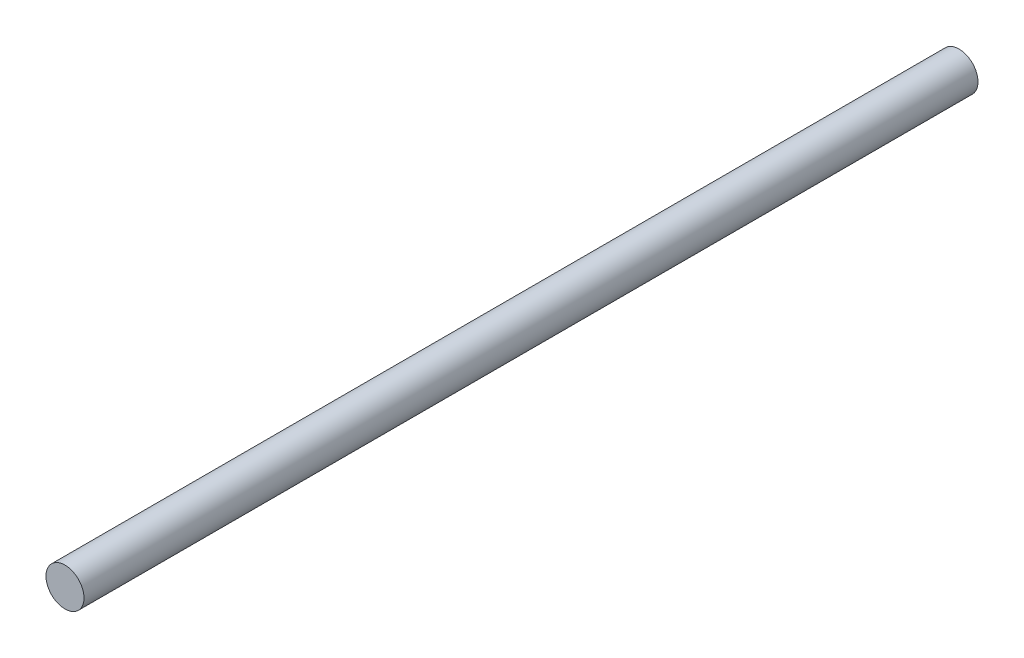
SolidWorks part; units mm, degrees
ref_plane "Front Plane" through (0, 0, 0) normal (0, 0, 1) x (1, 0, 0)
ref_plane "Top Plane" through (0, 0, 0) normal (0, 1, 0) x (1, 0, 0)
ref_plane "Right Plane" through (0, 0, 0) normal (1, 0, 0) x (0, 0, -1)
sketch "Sketch1" plane through (0, 0, 0) normal (0, 0, 1) x (1, 0, 0)
  circle A0 centre (0, 0) radius 1
extrude "Boss-Extrude1" add sketch "Sketch1" against normal blind 22 and the other way blind 25
